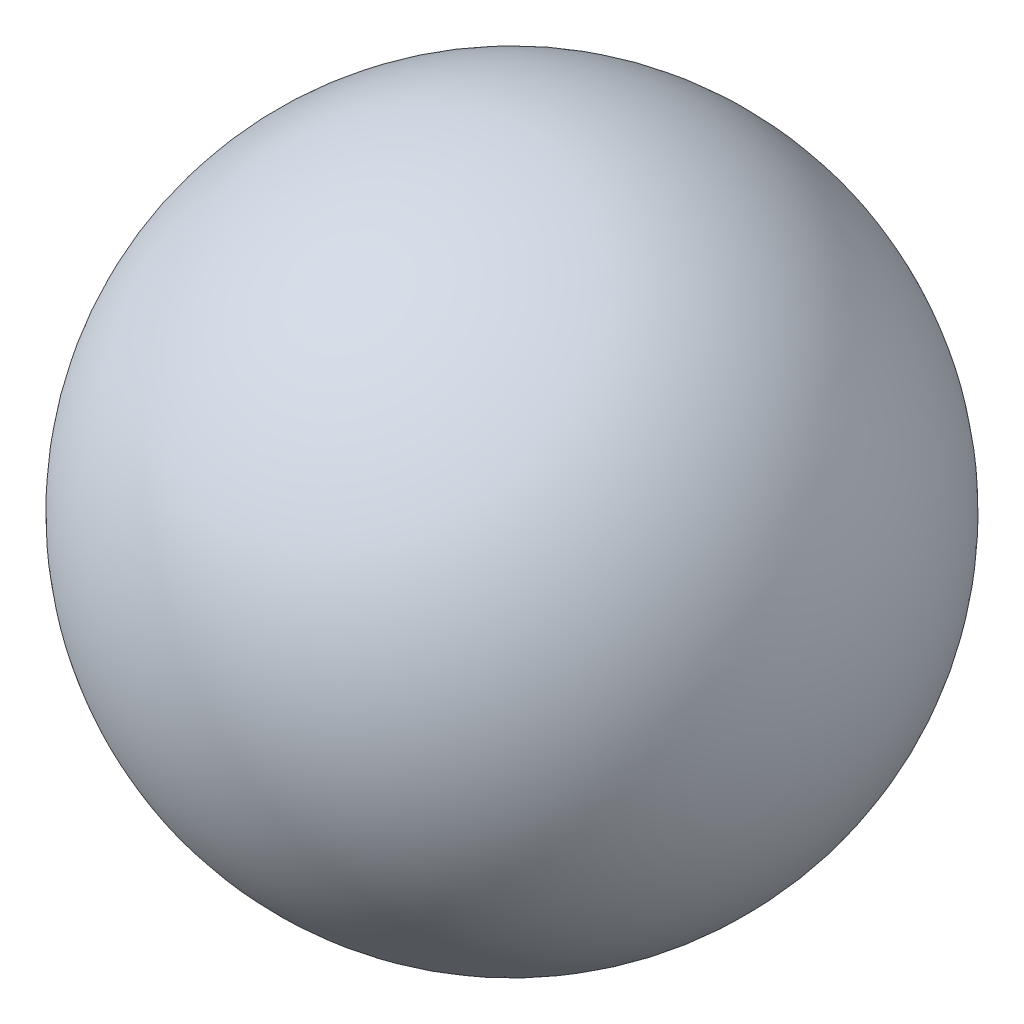
SolidWorks part; units mm, degrees
ref_plane "Front Plane" through (0, 0, 0) normal (0, 0, 1) x (1, 0, 0)
ref_plane "Top Plane" through (0, 0, 0) normal (0, 1, 0) x (1, 0, 0)
ref_plane "Right Plane" through (0, 0, 0) normal (1, 0, 0) x (0, 0, -1)
sketch "Sketch2" plane through (0, 0, 0) normal (1, 0, 0) x (0, 0, -1)
  line L0 (0, 0) -> (5.0314, 0) construction
  line L1 (2.35, 0) -> (-2.35, 0)
  arc A0 (-2.35, 0) -> (2.35, 0) centre (0, 0) ccw
  dimension "D1" = 4.7
revolve "Revolve1" add sketch "Sketch2" angle 360 about L0
